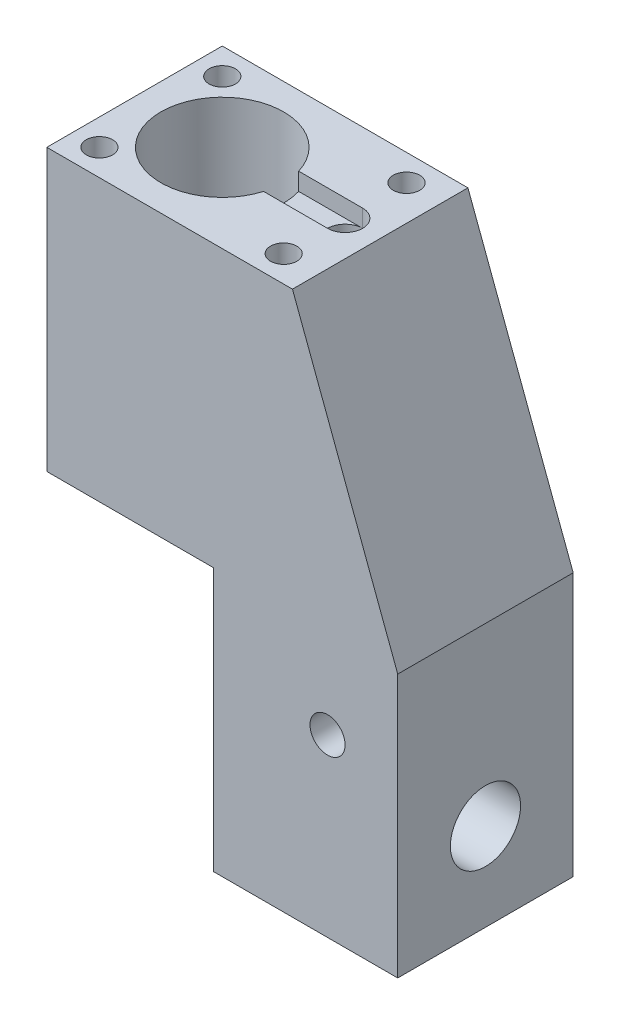
SolidWorks part; units mm, degrees
ref_plane "Front Plane" through (0, 0, 0) normal (0, 0, 1) x (1, 0, 0)
ref_plane "Top Plane" through (0, 0, 0) normal (0, 1, 0) x (1, 0, 0)
ref_plane "Right Plane" through (0, 0, 0) normal (1, 0, 0) x (0, 0, -1)
sketch "Sketch1" plane through (0, 0, 0) normal (0, 0, 1) x (1, 0, 0)
  line L0 (0, 0) -> (0, -30)
  line L1 (0, -30) -> (-21, -30)
  line L2 (-21, -30) -> (-21, 0)
  line L3 (-21, 0) -> (-40, 0)
  line L4 (-40, 0) -> (-40, 32)
  line L5 (-40, 32) -> (-12, 32)
  line L6 (-12, 32) -> (0, 0)
  dimension "D1" = 21
  dimension "D2" = 62
  dimension "D3" = 30
  dimension "D4" = 40
  dimension "D5" = 12
extrude "Boss-Extrude1" add sketch "Sketch1" along normal blind 20
sketch "Sketch2" plane through (0, 32, 0) normal (0, 1, 0) x (1, 0, 0)
  line L0 (-40, -20) -> (-40, 0) construction
  line L1 (-12, 0) -> (-40, 0) construction
  circle A0 centre (-30, -10) radius 7
  dimension "D2" = 14
  dimension "D1" = 10
  dimension "D3" = 10
extrude "Cut-Extrude1" cut sketch "Sketch2" against normal through all
sketch "Sketch3" plane through (0, 0, 0) normal (1, 0, 0) x (0, 0, -1)
  line L0 (-20, -30) -> (0, -30) construction
  line L1 (-20, -30) -> (-20, 0) construction
  circle A0 centre (-10, -20) radius 4
  dimension "D3" = 8
  dimension "D1" = 10
  dimension "D2" = 10
extrude "Cut-Extrude2" cut sketch "Sketch3" against normal through all
sketch "Sketch4" plane through (0, 32, 0) normal (0, 1, 0) x (1, 0, 0)
  line L0 (-12, 0) -> (-40, 0) construction
  line L1 (0, -20) -> (0, 0) construction
  circle A0 centre (-16, -10) radius 2
  dimension "D2" = 4
  dimension "D1" = 10
  dimension "D3" = 16
extrude "Cut-Extrude3" cut sketch "Sketch4" against normal blind 30
sketch "Sketch5" plane through (0, 32, 0) normal (0, 1, 0) x (1, 0, 0)
  line L0 (-16, -10) -> (-23, -10) construction
  line L1 (-16, -12) -> (-23.2918, -12)
  line L2 (-16, -8) -> (-23.2918, -8)
  circle A0 centre (-30, -10) radius 7 construction
  arc A1 (-16, -12) -> (-16, -8) centre (-16, -10) ccw
  arc A2 (-23.2918, -12) -> (-23.2918, -8) centre (-30, -10) ccw
  dimension "D1" = 4
  dimension "D2" = 14
extrude "Cut-Extrude5" cut sketch "Sketch5" against normal blind 2
sketch "Sketch6" plane through (0, 0, 20) normal (0, 0, 1) x (1, 0, 0)
  line L1 (0, -30) -> (0, 0) construction
  line L2 (-21, -30) -> (0, -30) construction
  circle A0 centre (-8, -10) radius 2
  dimension "D3" = 4
  dimension "D1" = 8
  dimension "D2" = 20
extrude "Cut-Extrude6" cut sketch "Sketch6" against normal through all
sketch "Sketch7" plane through (-40, 0, 0) normal (-1, 0, 0) x (0, 0, 1)
  line L0 (20, 32) -> (0, 32) construction
  line L1 (20, 32) -> (20, 0) construction
  circle A0 centre (7, 15) radius 1.6
  circle A1 centre (13, 15) radius 1.6
  dimension "D2" = 3.2
  dimension "D3" = 3.2
  dimension "D1" = 6
  dimension "D4" = 17
  dimension "D5" = 7
extrude "Cut-Extrude7" cut sketch "Sketch7" against normal up to surface (3.1414 mm away)
sketch "Sketch8" plane through (0, 32, 0) normal (0, 1, 0) x (1, 0, 0)
  line L0 (-40, -20) -> (-40, 0) construction
  line L1 (-12, -20) -> (-40, -20) construction
  circle A0 centre (-37, -3) radius 1.5
  circle A1 centre (-37, -17) radius 1.5
  circle A2 centre (-16, -3) radius 1.5
  circle A3 centre (-16, -17) radius 1.5
  dimension "D1" = 3
  dimension "D2" = 24
  dimension "D3" = 3
  dimension "D4" = 14
  dimension "D5" = 3
sketch "Sketch9" plane through (0, 32, 0) normal (0, 1, 0) x (1, 0, 0)
  point P0 (-37, -3)
  point P3 (-16, -3)
  point P6 (-16, -17)
  point P9 (-37, -17)
hole_wizard "M3 Tapped Hole1" positions "Sketch9" profile "Sketch10" tap size "M3" standard "DIN"
sketch "Sketch10" plane through (-37, 32, 3) normal (1, 0, 0) x (0, 0, 1)
  line L0 (0, 0) -> (0, 8.2511)
  line L1 (0, 8.2511) -> (1.25, 7.5)
  line L2 (1.25, 7.5) -> (1.25, 6)
  line L3 (1.25, 6) -> (1.5, 6)
  line L4 (1.5, 6) -> (1.5, 0)
  line L5 (1.5, 0) -> (0, 0)
  line L10 (0, 8.2511) -> (-1.25, 7.5) construction
  line L11 (0, -6.35) -> (0, 107.95) construction
  dimension "Tap Drill Dia." = 2.5
  dimension "Tap Drill Depth" = 7.5
  dimension "Thread Major Dia." = 3
  dimension "Thread Depth" = 6
  dimension "Drill Angle" = 118
sketch "Sketch11" plane through (0, -30, 0) normal (0, -1, 0) x (1, 0, 0)
  line L0 (0, 20) -> (0, 0) construction
  line L1 (-21, 20) -> (0, 20) construction
  circle A0 centre (-8, 10) radius 2
  circle A1 centre (-16, 10) radius 2
  dimension "D1" = 4
  dimension "D5" = 4
  dimension "D2" = 8
  dimension "D3" = 8
  dimension "D4" = 10
extrude "Cut-Extrude8" cut sketch "Sketch11" against normal blind 20
sketch "Sketch12" plane through (0, 2, 0) normal (0, 1, 0) x (1, 0, 0)
  circle A0 centre (-16, -10) radius 1.5
  dimension "D1" = 3
extrude "Cut-Extrude9" cut sketch "Sketch12" against normal up to surface (12 mm away) up to face at (-14, -10, 10)
